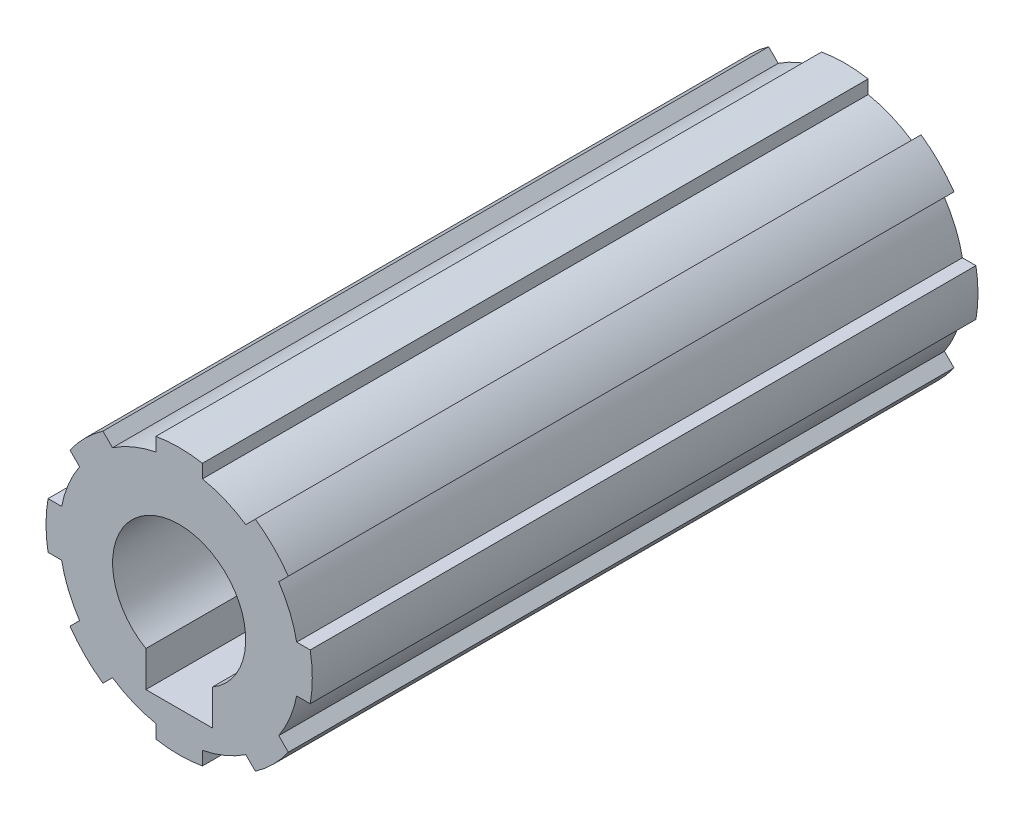
SolidWorks part; units mm, degrees
ref_plane "Front" through (0, 0, 0) normal (0, 0, 1) x (1, 0, 0)
ref_plane "Top" through (0, 0, 0) normal (0, 1, 0) x (1, 0, 0)
ref_plane "Right" through (0, 0, 0) normal (1, 0, 0) x (0, 0, -1)
sketch "Sketch1" plane through (0, 0, 0) normal (0, 0, 1) x (1, 0, 0)
  circle A0 centre (0, 0) radius 18
  dimension "d" = 36
extrude "BaseKey" add sketch "Sketch1" along normal mid plane 100
sketch "Sketch2" plane through (0, 0, 0) normal (0, 0, 1) x (1, 0, 0)
  line L0 (0, 9.5196) -> (0, -9.8317) construction
  line L1 (-3.5, 19.6914) -> (-3.5, 0)
  line L2 (-3.5, 0) -> (3.5, 0)
  line L3 (3.5, 0) -> (3.5, 19.6914)
  arc A0 (3.5, 19.6914) -> (-3.5, 19.6914) centre (0, 0) ccw
  dimension "D" = 40
  dimension "B" = 7
  dimension "B1" = 3.5
extrude "Rectangle" add sketch "Sketch2" along normal mid plane 100
pattern_circular "RectanglePat" count 8 over 360 about axis through (0, 0, 0) along (0, 0, 1) of "Rectangle"
sketch "草图1" plane through (0, 0, 50) normal (0, 0, 1) x (1, 0, 0)
  circle A0 centre (0, 0) radius 10
extrude "切除-拉伸1" cut sketch "草图1" against normal blind 22
sketch "草图2" plane through (0, 0, 0) normal (0, 1, 0) x (1, 0, 0)
  line L0 (0, -72.488) -> (0, 61.8075) construction
  line L1 (0, -50) -> (5, -50)
  line L2 (-3.5, -50) -> (3.5, -50) construction
  line L3 (3.5, -50) -> (10.0101, -50) construction
  line L4 (5, -50) -> (5, -43)
  line L5 (-5, -43) -> (-5, -50)
  line L6 (-10.0101, -50) -> (-3.5, -50) construction
  line L7 (-5, -50) -> (0, -50)
  line L8 (5, -43) -> (5, -36)
  line L9 (5, -36) -> (5, -28)
  line L10 (-5, -36) -> (-5, -43)
  line L11 (5, -28) -> (-5, -28)
  line L12 (-5, -28) -> (-5, -36)
extrude "切除-拉伸2" cut sketch "草图2" against normal blind 14
equation "\"B1@Sketch2\" = \"B@Sketch2\" / 2"
equation "\"L1@Rectangle\" = \"L@BaseKey\""
